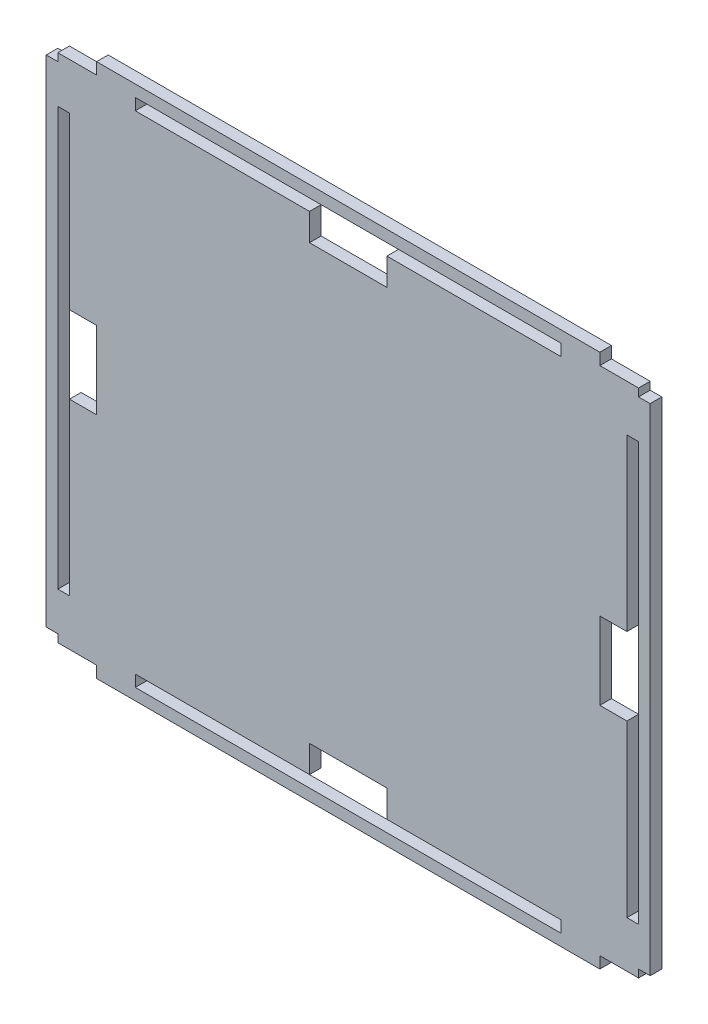
SolidWorks part; units mm, degrees
ref_plane "Front Plane" through (0, 0, 0) normal (0, 0, 1) x (1, 0, 0)
ref_plane "Top Plane" through (0, 0, 0) normal (0, 1, 0) x (1, 0, 0)
ref_plane "Right Plane" through (0, 0, 0) normal (1, 0, 0) x (0, 0, -1)
sketch "Sketch1" plane through (0, 0, 0) normal (0, 0, 1) x (1, 0, 0)
  line L1 (-96.3592, 44.8337) -> (59.6408, 44.8337)
  line L2 (-96.3592, 44.8337) -> (-96.3592, -93.1663)
  line L3 (-96.3592, -93.1663) -> (59.6408, -93.1663)
  line L4 (59.6408, 44.8337) -> (59.6408, -93.1663)
  line L7 (59.6408, 39.8337) -> (56.6408, 39.8337)
  line L8 (46.6408, 44.8337) -> (46.6408, 41.8337)
  line L11 (46.6408, 41.8337) -> (56.6408, 41.8337)
  line L12 (56.6408, 39.8337) -> (56.6408, 41.8337)
  line L13 (-73.3592, 41.8337) -> (36.6408, 41.8337)
  line L14 (-73.3592, 41.8337) -> (-73.3592, 38.8337)
  line L15 (-73.3592, 38.8337) -> (36.6408, 38.8337)
  line L16 (-93.3592, 39.8337) -> (-93.3592, 41.8337)
  line L17 (-83.3592, 41.8337) -> (-93.3592, 41.8337)
  line L20 (-83.3592, 44.8337) -> (-83.3592, 41.8337)
  line L21 (-96.3592, 39.8337) -> (-93.3592, 39.8337)
  line L26 (-96.3592, -88.1663) -> (-93.3592, -88.1663)
  line L27 (-83.3592, -93.1663) -> (-83.3592, -90.1663)
  line L30 (-83.3592, -90.1663) -> (-93.3592, -90.1663)
  line L31 (-93.3592, -88.1663) -> (-93.3592, -90.1663)
  line L32 (56.6408, -88.1663) -> (56.6408, -90.1663)
  line L33 (46.6408, -90.1663) -> (56.6408, -90.1663)
  line L36 (46.6408, -93.1663) -> (46.6408, -90.1663)
  line L37 (59.6408, -88.1663) -> (56.6408, -88.1663)
  line L40 (36.6408, 41.8337) -> (36.6408, 38.8337)
  line L42 (-28.3592, 38.8337) -> (-28.3592, 31.8337)
  line L43 (-28.3592, 31.8337) -> (-8.3592, 31.8337)
  line L44 (-8.3592, 38.8337) -> (-8.3592, 31.8337)
  line L45 (-93.3592, 29.8337) -> (-90.3592, 29.8337)
  line L46 (-93.3592, 29.8337) -> (-93.3592, -78.1663)
  line L47 (-93.3592, -78.1663) -> (-90.3592, -78.1663)
  line L48 (-90.3592, 29.8337) -> (-90.3592, -78.1663)
  line L49 (-90.3592, -14.1663) -> (-83.3592, -14.1663)
  line L51 (-90.3592, -34.1663) -> (-83.3592, -34.1663)
  line L52 (-83.3592, -14.1663) -> (-83.3592, -34.1663)
  line L54 (-8.3592, -87.1663) -> (-8.3592, -80.1663)
  line L55 (-28.3592, -80.1663) -> (-8.3592, -80.1663)
  line L56 (-28.3592, -87.1663) -> (-28.3592, -80.1663)
  line L58 (36.6408, -90.1663) -> (36.6408, -87.1663)
  line L59 (-73.3592, -87.1663) -> (36.6408, -87.1663)
  line L60 (-73.3592, -90.1663) -> (-73.3592, -87.1663)
  line L61 (-73.3592, -90.1663) -> (36.6408, -90.1663)
  line L62 (46.6408, -14.1663) -> (46.6408, -34.1663)
  line L63 (53.6408, -34.1663) -> (46.6408, -34.1663)
  line L65 (53.6408, -14.1663) -> (46.6408, -14.1663)
  line L66 (53.6408, 29.8337) -> (53.6408, -78.1663)
  line L67 (56.6408, -78.1663) -> (53.6408, -78.1663)
  line L68 (56.6408, 29.8337) -> (56.6408, -78.1663)
  line L69 (56.6408, 29.8337) -> (53.6408, 29.8337)
  point P13 (-18.3592, 44.8337)
  point P17 (-96.3592, -24.1663)
  point P38 (-8.3592, 35.3337)
  point P48 (0, 0)
  point P49 (0, 0)
  point P50 (-18.3592, 44.8337)
  point P51 (0, 0)
  point P52 (0, 0)
  point P53 (61.045, -24.1663)
  point P69 (0, 0)
  dimension "D1" = 156
  dimension "D2" = 138
  dimension "D5" = 10
  dimension "D6" = 2
  dimension "D8" = 3
  dimension "D9" = 110
  dimension "D10" = 10
  dimension "D11" = 3
  dimension "D12" = 7
  dimension "D13" = 20
  dimension "D14" = 45
  dimension "D15" = 20
  dimension "D16" = 7
  dimension "D17" = 3
  dimension "D18" = 108
  dimension "D19" = 44
  dimension "D20" = 10
  dimension "D21" = 3
extrude "Boss-Extrude1" add sketch "Sketch1" along normal blind 3 contours L37 L4 L7 L12 L11 L8 L1 L20 L17 L16 L21 L2 L26 L31 L30 L27 L3 L36 L33 L32 L69 L68 L67 L66 L63 L62 L65 L61 L60 L59 L56 L55 L54 L58 L15 L44 L43 L42 L14 L13 L40 L49 L52 L51
